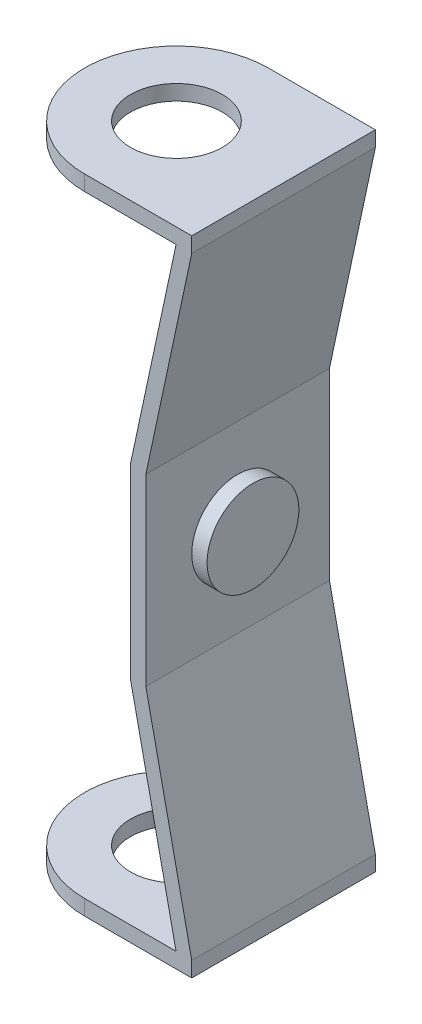
SolidWorks part; units mm, degrees
ref_plane "정면" through (0, 0, 0) normal (0, 0, 1) x (1, 0, 0)
ref_plane "윗면" through (0, 0, 0) normal (0, 1, 0) x (1, 0, 0)
ref_plane "우측면" through (0, 0, 0) normal (1, 0, 0) x (0, 0, -1)
sketch "스케치3" plane through (0, 0, 0) normal (0, 0, 1) x (1, 0, 0)
  line L0 (0, -30) -> (0, 30)
  line L1 (0, 30) -> (15, 100)
  line L2 (15, 100) -> (15, 105)
  line L3 (15, 105) -> (-50, 105)
  line L4 (-50, 105) -> (-50, 100)
  line L5 (-50, 100) -> (9.8865, 100)
  line L6 (9.8865, 100) -> (-5, 30.5297)
  line L7 (-5, 30.5297) -> (-5, -30.5297)
  line L8 (0, 0) -> (-20.3039, 0) construction
  line L9 (9.8865, -100) -> (-5, -30.5297)
  line L10 (-50, -100) -> (9.8865, -100)
  line L11 (-50, -105) -> (-50, -100)
  line L12 (15, -105) -> (-50, -105)
  line L13 (15, -100) -> (15, -105)
  line L14 (0, -30) -> (15, -100)
  point P11 (-5, 0)
  dimension "D1" = 5
  dimension "D2" = 5
  dimension "D3" = 5
  dimension "D4" = 65
  dimension "D5" = 105
  dimension "D6" = 30
  dimension "D7" = 15
extrude "보스-돌출2" add sketch "스케치3" along normal mid plane 60
sketch "스케치4" plane through (0, 105, 0) normal (0, 1, 0) x (1, 0, 0)
  line L0 (-20, 30) -> (-20, 33.1229)
  line L1 (-20, 33.1229) -> (-53.3935, 33.1229)
  line L2 (-53.3935, 33.1229) -> (-53.3935, -32.9575)
  line L3 (-53.3935, -32.9575) -> (-20, -32.9575)
  line L4 (-20, -32.9575) -> (-20, -30)
  circle A0 centre (-20, 0) radius 15
  arc A1 (-20, 30) -> (-20, -30) centre (-20, 0) ccw
  dimension "D1" = 30
  dimension "D2" = 60
  dimension "D3" = 20
extrude "컷-돌출1" cut sketch "스케치4" against normal blind 210
sketch "스케치5" plane through (-5, 0, 0) normal (-1, 0, 0) x (0, 0, 1)
  circle A0 centre (0, 0) radius 15
  dimension "D1" = 30
extrude "보스-돌출3" add sketch "스케치5" along normal mid plane 20
fillet "필렛1" radius 4 1 edges at (-15, 0, 15)
